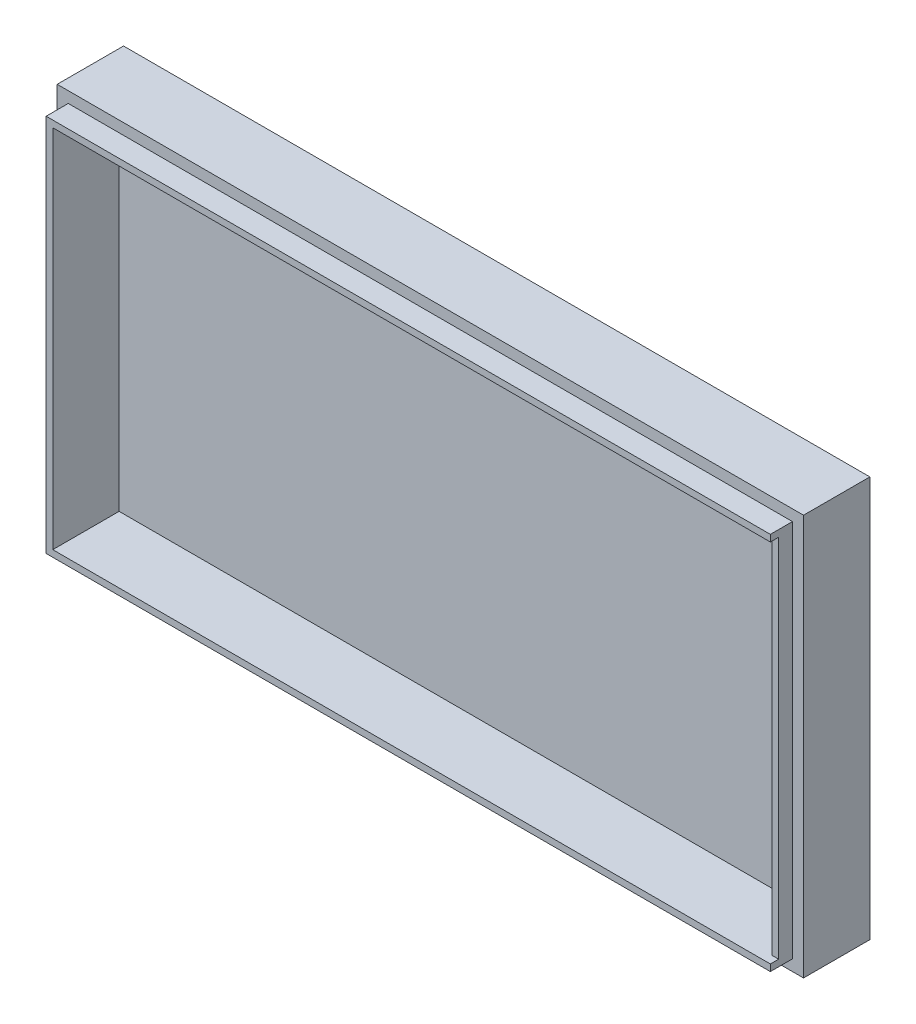
SolidWorks part; units mm, degrees
ref_plane "Front Plane" through (0, 0, 0) normal (0, 0, 1) x (1, 0, 0)
ref_plane "Top Plane" through (0, 0, 0) normal (0, 1, 0) x (1, 0, 0)
ref_plane "Right Plane" through (0, 0, 0) normal (1, 0, 0) x (0, 0, -1)
sketch "Sketch1" plane through (0, 0, 0) normal (0, 0, 1) x (1, 0, 0)
  line L1 (-4.8169, 4.162) -> (130.1831, 4.162)
  line L2 (-4.8169, 4.162) -> (-4.8169, -68.338)
  line L3 (-4.8169, -68.338) -> (130.1831, -68.338)
  line L4 (130.1831, 4.162) -> (130.1831, -68.338)
  dimension "D1" = 135
  dimension "D2" = 72.5
extrude "Boss-Extrude1" add sketch "Sketch1" along normal blind 12
sketch "Sketch2" plane through (0, 0, 12) normal (0, 0, 1) x (1, 0, 0)
  line L0 (130.1831, 4.162) -> (-4.8169, 4.162) construction
  line L1 (-2.8169, 2.162) -> (128.1831, 2.162)
  line L2 (-2.8169, 2.162) -> (-2.8169, -66.338)
  line L3 (-2.8169, -66.338) -> (128.1831, -66.338)
  line L4 (128.1831, 2.162) -> (128.1831, -66.338)
  line L5 (-4.8169, 4.162) -> (-4.8169, -68.338) construction
  line L6 (-4.8169, -68.338) -> (130.1831, -68.338) construction
  line L7 (130.1831, -68.338) -> (130.1831, 4.162) construction
  dimension "D1" = 2
  dimension "D2" = 2
  dimension "D3" = 2
  dimension "D4" = 2
extrude "Boss-Extrude2" add sketch "Sketch2" along normal blind 4
sketch "Sketch4" plane through (0, 0, 16) normal (0, 0, 1) x (1, 0, 0)
  line L0 (128.1831, 2.162) -> (-2.8169, 2.162) construction
  line L1 (-1.6169, 0.962) -> (126.9831, 0.962)
  line L2 (-1.6169, 0.962) -> (-1.6169, -65.138)
  line L3 (-1.6169, -65.138) -> (126.9831, -65.138)
  line L4 (126.9831, 0.962) -> (126.9831, -65.138)
  line L5 (-2.8169, 2.162) -> (-2.8169, -66.338) construction
  line L6 (128.1831, -66.338) -> (128.1831, 2.162) construction
  line L7 (-2.8169, -66.338) -> (128.1831, -66.338) construction
  dimension "D1" = 1.2
  dimension "D2" = 1.2
  dimension "D3" = 1.2
  dimension "D4" = 1.2
extrude "Cut-Extrude1" cut sketch "Sketch4" against normal up to surface (4 mm away) up to face at (62.6831, -32.088, 12)
sketch "Sketch5" plane through (0, 0, 12) normal (0, 0, 1) x (1, 0, 0)
  line L1 (-1.6169, 0.962) -> (126.9831, 0.962)
  line L2 (-1.6169, 0.962) -> (-1.6169, -65.138)
  line L3 (-1.6169, -65.138) -> (126.9831, -65.138)
  line L4 (126.9831, 0.962) -> (126.9831, -65.138)
extrude "Cut-Extrude2" cut sketch "Sketch5" against normal blind 8
sketch "Sketch6" plane through (128.1831, 0, 0) normal (1, 0, 0) x (0, 0, -1)
  line L0 (-16, -66.338) -> (-16, 2.162) construction
  line L1 (-16, 0.962) -> (-14.5, 0.962)
  line L2 (-16, 0.962) -> (-16, -65.138)
  line L3 (-16, -65.138) -> (-14.5, -65.138)
  line L4 (-14.5, 0.962) -> (-14.5, -65.138)
  line L5 (-16, 2.162) -> (-12, 2.162) construction
  line L6 (-16, -66.338) -> (-12, -66.338) construction
  dimension "D1" = 1.2
  dimension "D2" = 1.2
  dimension "D3" = 1.5
extrude "Cut-Extrude3" cut sketch "Sketch6" against normal blind 10
